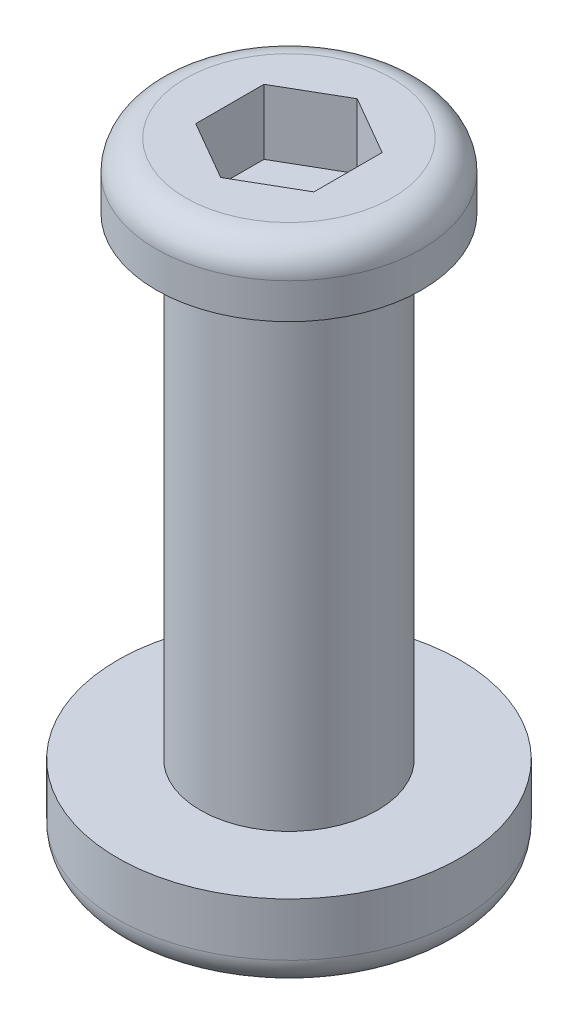
SolidWorks part; units mm, degrees
material "AISI 304"
ref_plane "前视基准面" through (0, 0, 0) normal (0, 0, 1) x (1, 0, 0)
ref_plane "上视基准面" through (0, 0, 0) normal (0, 1, 0) x (1, 0, 0)
ref_plane "右视基准面" through (0, 0, 0) normal (1, 0, 0) x (0, 0, -1)
other "Configuration Table"
sketch "草图1" plane through (0, 0, 0) normal (0, 1, 0) x (1, 0, 0)
  circle A0 centre (0, 0) radius 1.5
  dimension "D1" = 3
extrude "凸台-拉伸1" add sketch "草图1" along normal blind 8
sketch "草图2" plane through (0, 8, 0) normal (0, 1, 0) x (1, 0, 0)
  line L0 (0, 0) -> (0, 1.8449) construction
  line L1 (0, 1.1547) -> (-1, 0.5774)
  line L2 (-1, 0.5774) -> (-1, -0.5774)
  line L3 (-1, -0.5774) -> (0, -1.1547)
  line L4 (0, -1.1547) -> (1, -0.5774)
  line L5 (1, -0.5774) -> (1, 0.5774)
  line L6 (1, 0.5774) -> (0, 1.1547)
  circle A0 centre (0, 0) radius 2.25
  circle A1 centre (0, 0) radius 1 construction
  dimension "D2" = 4.5
  dimension "D1" = 2
extrude "凸台-拉伸2" add sketch "草图2" along normal blind 1.1
sketch "草图3" plane through (0, 0, 0) normal (0, -1, 0) x (1, 0, 0)
  line L0 (0, 0) -> (0, 3.3681) construction
  line L1 (0, 1.1547) -> (-1, 0.5774)
  line L2 (-1, 0.5774) -> (-1, -0.5774)
  line L3 (-1, -0.5774) -> (0, -1.1547)
  line L4 (0, -1.1547) -> (1, -0.5774)
  line L5 (1, -0.5774) -> (1, 0.5774)
  line L6 (1, 0.5774) -> (0, 1.1547)
  circle A0 centre (0, 0) radius 2.9
  circle A1 centre (0, 0) radius 1 construction
  dimension "D2" = 5.8
  dimension "D1" = 2
extrude "凸台-拉伸3" add sketch "草图3" along normal blind 1.4
fillet "圆角1" radius 0.5 2 edges at (0, 9.1, 2.25) (0, -1.4, -2.9)
